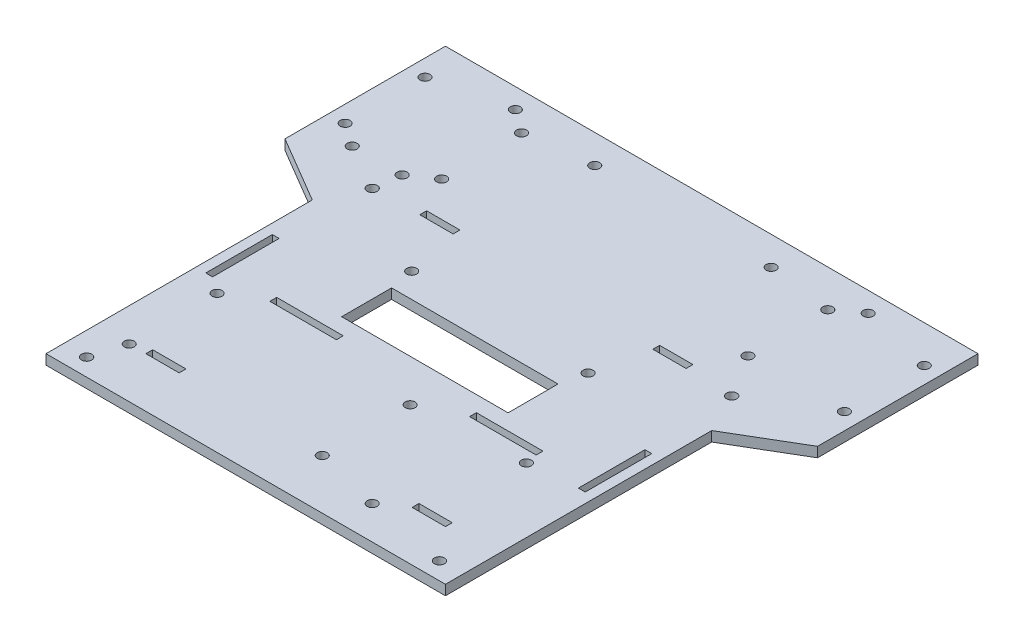
SolidWorks part; units mm, degrees
material "Perspex (TM) GS Acrylic Cast Sheet"
ref_plane "Front Plane" through (0, 0, 0) normal (0, 0, 1) x (1, 0, 0)
ref_plane "Top Plane" through (0, 0, 0) normal (0, 1, 0) x (1, 0, 0)
ref_plane "Right Plane" through (0, 0, 0) normal (1, 0, 0) x (0, 0, -1)
sketch "Sketch1" plane through (0, 0, 0) normal (0, 1, 0) x (1, 0, 0)
  line L0 (-60, 10) -> (-80, 21.7918)
  line L1 (60, -70) -> (-60, -70)
  line L2 (60, -70) -> (60, 70)
  line L3 (60, 70) -> (-60, 70)
  line L4 (-60, -70) -> (-60, 70)
  line L5 (60, -70) -> (-60, 70) construction
  line L6 (60, 70) -> (-60, -70) construction
  line L7 (-80, 21.7918) -> (-80, 70)
  line L8 (-80, 70) -> (-60, 70)
  line L9 (0, 0) -> (0, 70) construction
  line L10 (60, 10) -> (80, 21.7918)
  line L11 (80, 70) -> (60, 70)
  line L12 (80, 21.7918) -> (80, 70)
  point P0 (0, 0)
  dimension "D1" = 140
  dimension "D2" = 120
  dimension "D3" = 20
  dimension "D4" = 30.523
  dimension "D5" = 60
extrude "Boss-Extrude1" add sketch "Sketch1" along normal blind 3 contours L4 L1 L2 L3 | L8 L7 L0 L4 | L10 L12 L11 L2
sketch "Sketch2" plane through (0, 3, 0) normal (0, 1, 0) x (1, 0, 0)
  line L0 (60, -70) -> (60, 10) construction
  line L1 (-60, -70) -> (-60, 10) construction
  line L3 (60, -70) -> (-60, -70) construction
  circle A0 centre (28, -60) radius 1.5
  circle A1 centre (40.6, -26.277) radius 1.5
  circle A2 centre (-50, -55) radius 1.5
  circle A3 centre (8, -55) radius 1.5
  circle A4 centre (-50, -28.6) radius 1.5
  circle A5 centre (8, -28.6) radius 1.5
  dimension "D1" = 3
  dimension "D2" = 36
  dimension "D3" = 10
  dimension "D4" = 3
  dimension "D6" = 3
  dimension "D9" = 15
  dimension "D7" = 3
  dimension "D11" = 52
  dimension "D12" = 3
  dimension "D13" = 3
  dimension "12.6" = 12.6
  dimension "D8" = 58
  dimension "D10" = 15
  dimension "26.4" = 26.4
  dimension "D15" = 26.4
  dimension "D16" = 58
  dimension "D17" = 52
  dimension "D18" = 88
extrude "Cut-Extrude1" cut sketch "Sketch2" against normal through all
sketch "Sketch3" plane through (0, 3, 0) normal (0, 1, 0) x (1, 0, 0)
  line L0 (-0.0296, 57.8856) -> (-0.0296, -0.1144) construction
  line L1 (-30.0296, 33.8856) -> (29.9704, 33.8856) construction
  line L6 (-80, 21.7918) -> (-80, 70) construction
  line L7 (80, 70) -> (-80, 70) construction
  line L8 (-60, 10) -> (-60, 70) construction
  line L9 (60, 10) -> (60, 70) construction
  circle A0 centre (-26.5296, 61.3856) radius 1.5
  circle A1 centre (-26.5296, 6.3856) radius 1.5
  circle A2 centre (26.4704, 6.3856) radius 1.5
  circle A3 centre (26.4704, 61.3856) radius 1.5
  point P16 (-80, 45.8959)
  dimension "D1" = 53
  dimension "D2" = 36.1144
  dimension "D3" = 3
  dimension "D4" = 79.9704
  dimension "D5" = 55
extrude "Cut-Extrude3" cut sketch "Sketch3" against normal through all
sketch "Sketch4" plane through (0, 3, 0) normal (0, 1, 0) x (1, 0, 0)
  line L0 (-60.5, 58.8639) -> (-60.5, 32.8639) construction
  line L1 (-80, 21.7918) -> (-80, 70) construction
  line L2 (80, 70) -> (-80, 70) construction
  line L3 (0, 0) -> (0, 70) construction
  circle A0 centre (-75, 34.8639) radius 1.5
  circle A1 centre (-75, 58.8639) radius 1.5
  circle A2 centre (-46, 34.8639) radius 1.5
  circle A3 centre (-46, 58.8639) radius 1.5
  circle A4 centre (46, 58.8639) radius 1.5
  circle A5 centre (46, 34.8639) radius 1.5
  circle A6 centre (75, 34.8639) radius 1.5
  circle A7 centre (75, 58.8639) radius 1.5
  dimension "D1" = 3
  dimension "D2" = 3
  dimension "D5" = 5
  dimension "D6" = 11.1361
  dimension "D7" = 5
  dimension "D3" = 24
  dimension "D4" = 14.5
extrude "Cut-Extrude4" cut sketch "Sketch4" against normal through all
sketch "Sketch5" plane through (0, 3, 0) normal (0, 1, 0) x (1, 0, 0)
  line L0 (80, 70) -> (-80, 70) construction
  line L1 (-80, 21.7918) -> (-80, 70) construction
  circle A0 centre (-68, 30) radius 1.5
  circle A1 centre (-53, 30) radius 1.5
  dimension "D1" = 3
  dimension "D2" = 3
  dimension "D3" = 40
  dimension "D4" = 40
  dimension "D6" = 12
  dimension "D5" = 15
extrude "Cut-Extrude5" cut sketch "Sketch5" against normal blind 3
sketch "Sketch6" plane through (0, 3, 0) normal (0, 1, 0) x (1, 0, 0)
  line L0 (60, -70) -> (-60, -70) construction
  line L1 (-45, -52.95) -> (-35, -52.95)
  line L2 (-45, -52.95) -> (-45, -55)
  line L3 (-45, -55) -> (-35, -55)
  line L4 (-35, -52.95) -> (-35, -55)
  line L5 (-45, -52.95) -> (-35, -55) construction
  line L6 (-45, -55) -> (-35, -52.95) construction
  line L7 (-60, -70) -> (-60, 10) construction
  line L8 (0, 0) -> (0, -70) construction
  line L9 (35, -52.95) -> (35, -55)
  line L10 (45, -55) -> (35, -55)
  line L11 (45, -52.95) -> (45, -55)
  line L12 (45, -52.95) -> (35, -52.95)
  line L13 (20, -22.75) -> (20, -20.7)
  line L14 (-20, -22.75) -> (-40, -22.75)
  line L15 (-20, -22.75) -> (-20, -20.7)
  line L16 (-20, -20.7) -> (-40, -20.7)
  line L17 (-40, -22.75) -> (-40, -20.7)
  line L18 (-20, -22.75) -> (-40, -20.7) construction
  line L19 (-20, -20.7) -> (-40, -22.75) construction
  line L20 (20, -22.75) -> (40, -22.75)
  line L21 (40, -22.75) -> (40, -20.7)
  line L22 (20, -20.7) -> (40, -20.7)
  line L23 (-60, -30) -> (60, -30) construction
  line L24 (60, -70) -> (60, 10) construction
  line L25 (-30, -21.725) -> (60, -21.725) construction
  line L26 (30, 24.35) -> (30, 22.3)
  line L27 (-40, 24.35) -> (-30, 24.35)
  line L28 (-40, 24.35) -> (-40, 22.3)
  line L29 (-40, 22.3) -> (-30, 22.3)
  line L30 (-30, 24.35) -> (-30, 22.3)
  line L31 (-40, 24.35) -> (-30, 22.3) construction
  line L32 (-40, 22.3) -> (-30, 24.35) construction
  line L33 (40, 24.35) -> (40, 22.3)
  line L34 (40, 24.35) -> (30, 24.35)
  line L35 (40, 22.3) -> (30, 22.3)
  circle A0 centre (-53, -64.8) radius 1.525
  circle A1 centre (53, -64.8) radius 1.525
  point P0 (-40, -53.975)
  point P16 (-30, -21.725)
  point P31 (-35, 23.325)
  dimension "D9" = 7
  dimension "D11" = 3.05
  dimension "D1" = 2.05
  dimension "D2" = 15
  dimension "D3" = 15
  dimension "D4" = 10
  dimension "D5" = 2.05
  dimension "D6" = 30.2
  dimension "D7" = 20
  dimension "D8" = 20
  dimension "D10" = 5.2
  dimension "D12" = 10
  dimension "D13" = 5
  dimension "D14" = 2.05
  dimension "D15" = 43
extrude "Cut-Extrude7" cut sketch "Sketch6" against normal through all
sketch "Sketch9" plane through (0, 3, 0) normal (0, 1, 0) x (1, 0, 0)
  line L0 (80, 70) -> (-80, 70) construction
  line L1 (-80, 21.7918) -> (-80, 70) construction
  line L2 (0, 0) -> (0, 70) construction
  circle A0 centre (-54, 22) radius 1.525
  circle A2 centre (54, 22) radius 1.525
  dimension "D1" = 3.05
  dimension "D2" = 48
  dimension "D3" = 26
extrude "Cut-Extrude8" cut sketch "Sketch9" against normal blind 3
sketch "Sketch10" plane through (0, 3, 0) normal (0, 1, 0) x (1, 0, 0)
  line L0 (60, -70) -> (60, 10) construction
  line L1 (24.8, -15.9751) -> (-25.2, -15.9751)
  line L2 (24.8, -15.9751) -> (24.8, -0.9751)
  line L3 (24.8, -0.9751) -> (-25.2, -0.9751)
  line L4 (-25.2, -15.9751) -> (-25.2, -0.9751)
  line L5 (24.8, -15.9751) -> (-25.2, -0.9751) construction
  line L6 (24.8, -0.9751) -> (-25.2, -15.9751) construction
  line L7 (80, 70) -> (-80, 70) construction
  point P0 (-0.2, -8.4751)
  dimension "D1" = 15
  dimension "D2" = 50
  dimension "D3" = 35.2
  dimension "D4" = 70.9751
extrude "Cut-Extrude9" cut sketch "Sketch10" against normal blind 5
sketch "Sketch11" plane through (0, 3, 0) normal (0, 1, 0) x (1, 0, 0)
  line L0 (80, 70) -> (-80, 70) construction
  line L1 (0, 0) -> (0, 70) construction
  line L2 (-80, 21.7918) -> (-80, 70) construction
  circle A0 centre (-53, 64) radius 1.5
  circle A1 centre (53, 64) radius 1.5
  dimension "D1" = 3
  dimension "D3" = 27
  dimension "D2" = 6
extrude "Cut-Extrude10" cut sketch "Sketch11" against normal blind 5
sketch "Sketch12" plane through (0, 3, 0) normal (0, 1, 0) x (1, 0, 0)
  line L0 (80, 70) -> (-80, 70) construction
  line L1 (-57, -5) -> (-54.95, -5)
  line L2 (-57, -5) -> (-57, -25)
  line L3 (-57, -25) -> (-54.95, -25)
  line L4 (-54.95, -5) -> (-54.95, -25)
  line L5 (-57, -5) -> (-54.95, -25) construction
  line L6 (-57, -25) -> (-54.95, -5) construction
  line L13 (-60, -70) -> (-60, 10) construction
  line L14 (60, -70) -> (-60, -70) construction
  line L15 (0, 0) -> (0, -70) construction
  line L20 (54.95, -5) -> (54.95, -25)
  line L21 (57, -25) -> (54.95, -25)
  line L22 (57, -5) -> (57, -25)
  line L23 (57, -5) -> (54.95, -5)
  point P0 (-55.975, -15)
  dimension "D1" = 20
  dimension "D2" = 75
  dimension "D3" = 2.05
  dimension "D4" = 3
extrude "Cut-Extrude11" cut sketch "Sketch12" against normal blind 10
